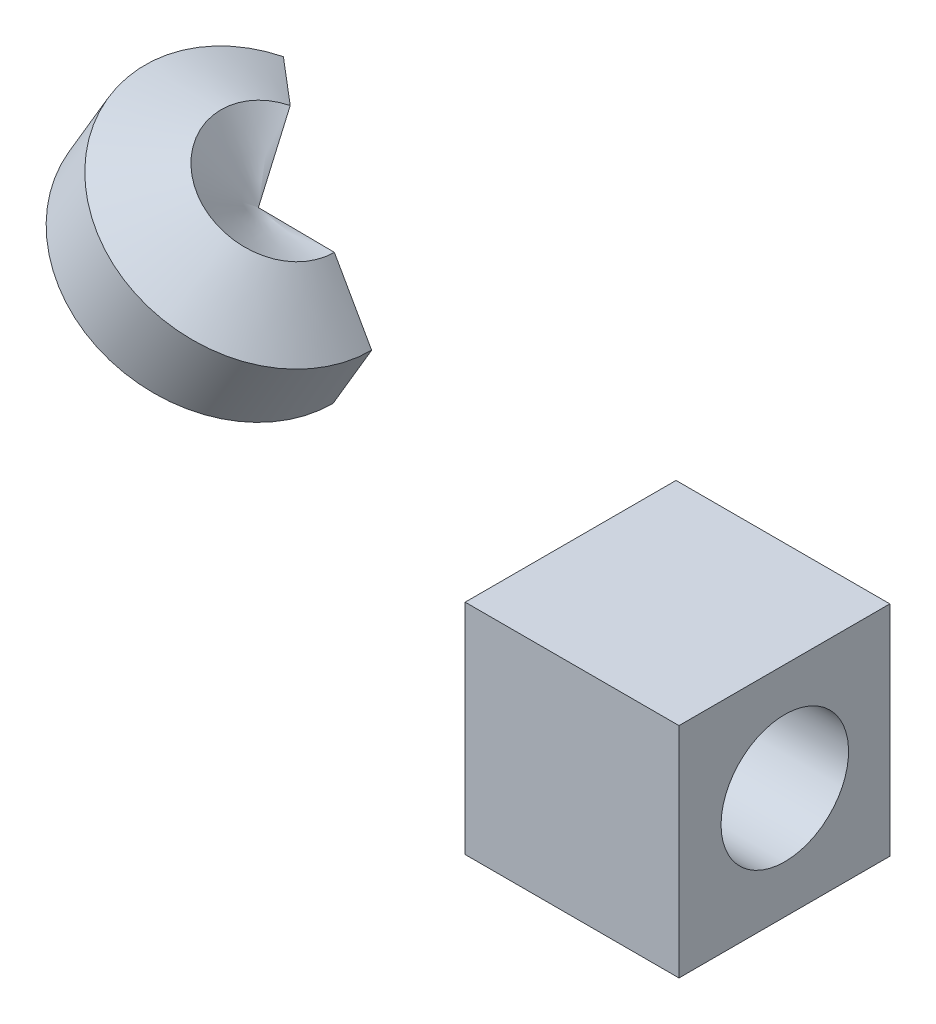
SolidWorks part; units mm, degrees
ref_plane "前视基准面" through (0, 0, 0) normal (0, 0, 1) x (1, 0, 0)
ref_plane "上视基准面" through (0, 0, 0) normal (0, 1, 0) x (1, 0, 0)
ref_plane "右视基准面" through (0, 0, 0) normal (1, 0, 0) x (0, 0, -1)
sketch "草图1" plane through (0, 0, 0) normal (0, 0, 1) x (1, 0, 0)
  line L1 (-15.6614, 30.4258) -> (6.6472, 30.4258)
  line L2 (-15.6614, 30.4258) -> (-15.6614, 7.6191)
  line L3 (-15.6614, 7.6191) -> (6.6472, 7.6191)
  line L4 (6.6472, 30.4258) -> (6.6472, 7.6191)
extrude "凸台-拉伸1" add sketch "草图1" along normal blind 22
sketch "草图11" plane through (-15.6614, 0, 0) normal (-1, 0, 0) x (0, 0, 1)
  circle A0 centre (10.9598, 19.2586) radius 6.6525
extrude "切除-拉伸1" cut sketch "草图11" against normal blind 33
ref_plane "基准面1" through (-15.6614, 30.4258, 22) normal (-1, 0, 0) x (0, 0, 1)
sketch "草图16" plane through (-29.5569, 29.6438, 22) normal (0, 0, 1) x (1, 0, 0)
  line L1 (0.1046, 11.8391) -> (4.1379, 18.662)
  line L2 (4.1379, 18.662) -> (0.2457, 25.5665)
  line L3 (0.2457, 25.5665) -> (-7.6798, 25.6479)
  line L4 (-7.6798, 25.6479) -> (-11.7131, 18.825)
  line L5 (-11.7131, 18.825) -> (-7.8209, 11.9206)
  line L6 (-7.8209, 11.9206) -> (0.1046, 11.8391)
  circle A0 centre (-3.7876, 18.7435) radius 6.8641 construction
revolve "旋转1" add sketch "草图16" angle 229 about L4
